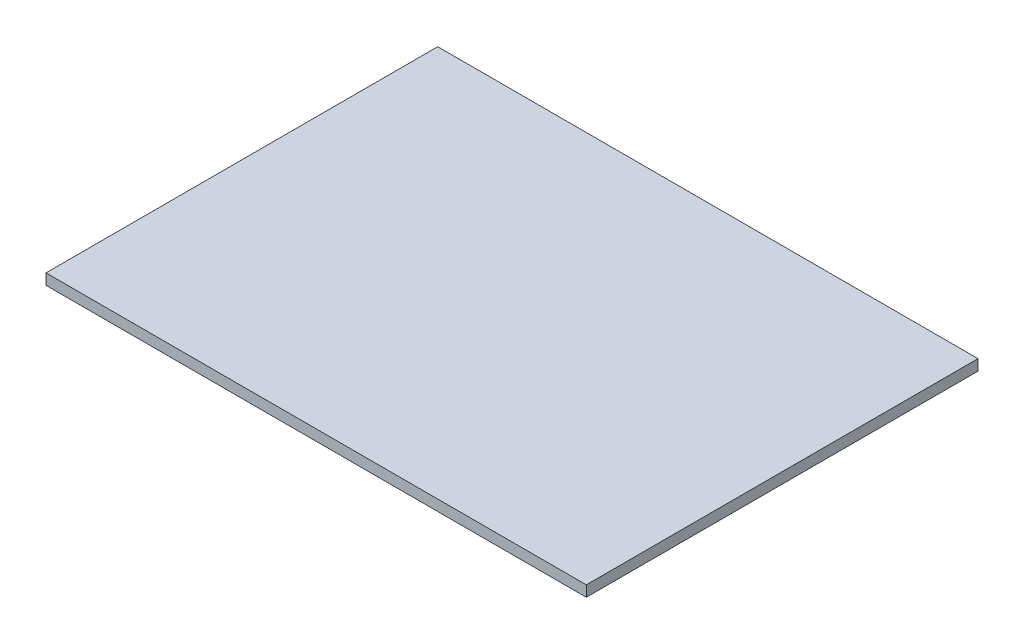
SolidWorks part; units mm, degrees
ref_plane "Front Plane" through (0, 0, 0) normal (0, 0, 1) x (1, 0, 0)
ref_plane "Top Plane" through (0, 0, 0) normal (0, 1, 0) x (1, 0, 0)
ref_plane "Right Plane" through (0, 0, 0) normal (1, 0, 0) x (0, 0, -1)
sketch "Sketch1" plane through (0, 0, 0) normal (0, 1, 0) x (1, 0, 0)
  line L1 (-317.5, -230.1875) -> (317.5, -230.1875)
  line L2 (-317.5, -230.1875) -> (-317.5, 230.1875)
  line L3 (-317.5, 230.1875) -> (317.5, 230.1875)
  line L4 (317.5, -230.1875) -> (317.5, 230.1875)
  line L5 (-317.5, -230.1875) -> (317.5, 230.1875) construction
  line L6 (-317.5, 230.1875) -> (317.5, -230.1875) construction
  point P0 (0, 0)
  dimension "D1" = 460.375
  dimension "D2" = 635
extrude "Boss-Extrude1" add sketch "Sketch1" along normal blind 12.7
